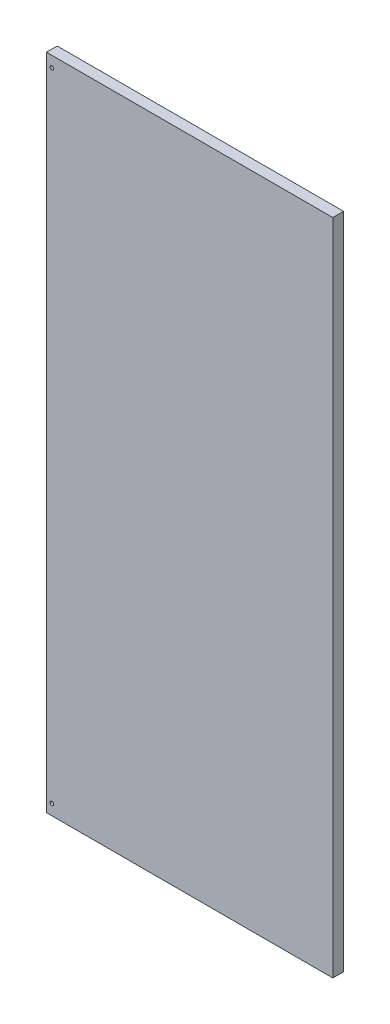
SolidWorks part; units mm, degrees
ref_plane "Alzado" through (0, 0, 0) normal (0, 0, 1) x (1, 0, 0)
ref_plane "Planta" through (0, 0, 0) normal (0, 1, 0) x (1, 0, 0)
ref_plane "Vista lateral" through (0, 0, 0) normal (1, 0, 0) x (0, 0, -1)
sketch "Croquis1" plane through (0, 0, 0) normal (0, 0, 1) x (1, 0, 0)
  line L1 (-378.8393, 25.8929) -> (21.1607, 25.8929)
  line L2 (-378.8393, 25.8929) -> (-378.8393, -894.1071)
  line L3 (-378.8393, -894.1071) -> (21.1607, -894.1071)
  line L4 (21.1607, 25.8929) -> (21.1607, -894.1071)
  line L5 (-378.8393, 25.8929) -> (21.1607, -894.1071) construction
  line L6 (-378.8393, -894.1071) -> (21.1607, 25.8929) construction
  point P0 (-178.8393, -434.1071)
  dimension "D1" = 400
  dimension "D2" = 920
extrude "Saliente-Extruir1" add sketch "Croquis1" against normal blind 15
sketch "Croquis3" plane through (0, 0, 0) normal (0, 0, 1) x (1, 0, 0)
  line L0 (-378.8393, -36.7156) -> (-371.3393, -36.7156) construction
  line L1 (-378.8393, 25.8929) -> (-378.8393, -894.1071) construction
  line L2 (-371.3393, 25.8929) -> (-371.3393, 10.8929) construction
  line L3 (21.1607, 25.8929) -> (-378.8393, 25.8929) construction
  line L4 (-378.8393, -894.1071) -> (-378.8393, -434.1071) construction
  line L5 (-378.8393, -434.1071) -> (0, -434.1071) construction
  line L6 (-371.3393, -894.1071) -> (-371.3393, -879.1071) construction
  line L7 (-378.8393, -831.4987) -> (-371.3393, -831.4987) construction
  circle A0 centre (-371.3393, 10.8929) radius 2.5
  circle A1 centre (-371.3393, -879.1071) radius 2.5
  dimension "D4" = 5
  dimension "D1" = 7.5
  dimension "D2" = 7.5
  dimension "D3" = 15
extrude "Cortar-Extruir1" cut sketch "Croquis3" against normal through all
